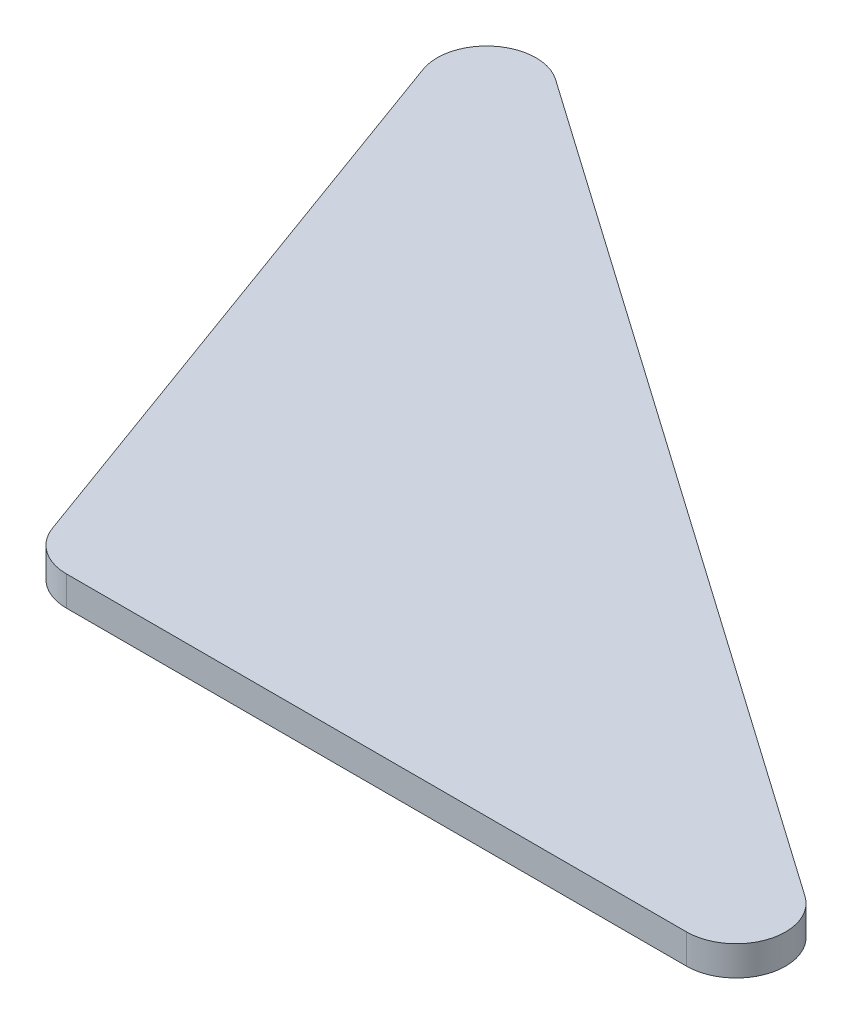
SolidWorks part; units mm, degrees
ref_plane "Front Plane" through (0, 0, 0) normal (0, 0, 1) x (1, 0, 0)
ref_plane "Top Plane" through (0, 0, 0) normal (0, 1, 0) x (1, 0, 0)
ref_plane "Right Plane" through (0, 0, 0) normal (1, 0, 0) x (0, 0, -1)
sketch "Sketch1" plane through (0, 0, 0) normal (0, 1, 0) x (1, 0, 0)
  line L0 (0, 0) -> (82, 0)
  line L1 (82, 0) -> (-28.0457, 77.0548)
  line L2 (-28.0457, 77.0548) -> (0, 0)
  dimension "D1" = 110
  dimension "D2" = 82
  dimension "D3" = 82
extrude "Boss-Extrude1" add sketch "Sketch1" along normal blind 3
fillet "Fillet1" radius 5 3 edges at (-28.0457, 1.5, -77.0548) (0, 1.5, 0) (82, 1.5, 0)
